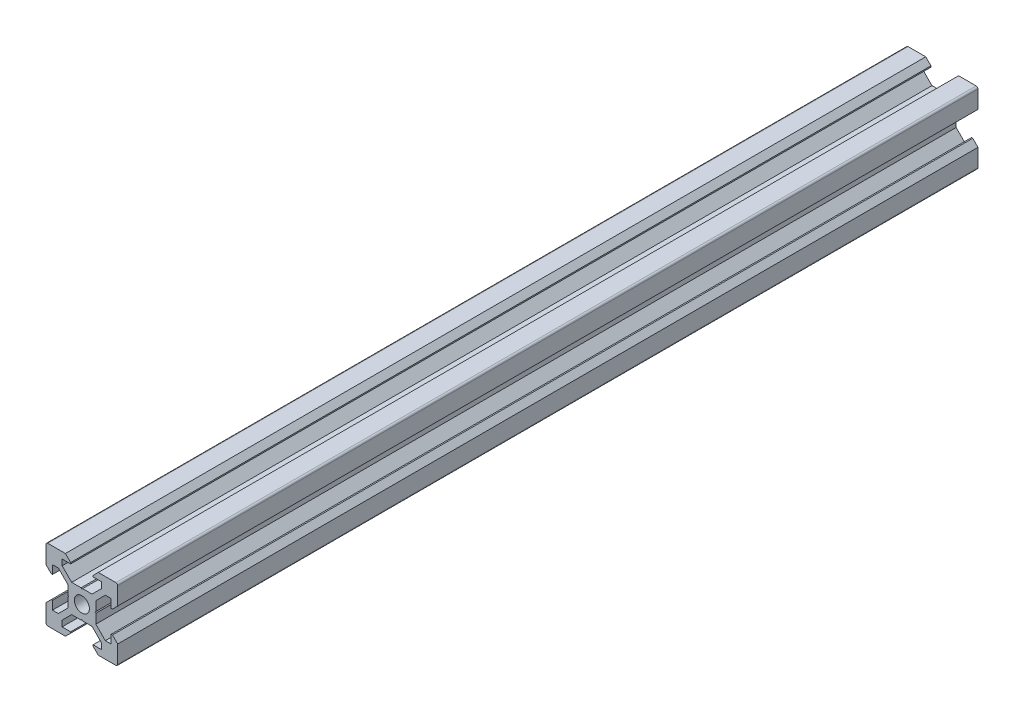
SolidWorks part; units mm, degrees
material "6061-T6 (SS)"
ref_plane "Front Plane" through (0, 0, 0) normal (0, 0, 1) x (1, 0, 0)
ref_plane "Top Plane" through (0, 0, 0) normal (0, 1, 0) x (1, 0, 0)
ref_plane "Right Plane" through (0, 0, 0) normal (1, 0, 0) x (0, 0, -1)
sketch "Sketch1" plane through (0, 0, 0) normal (0, 0, 1) x (1, 0, 0)
  line L1 (9.5, -10) -> (-9.5, -10)
  line L2 (10, -9.5) -> (10, 9.5)
  line L3 (9.5, 10) -> (-9.5, 10)
  line L4 (-10, -9.5) -> (-10, 9.5)
  line L5 (10, -10) -> (-10, 10) construction
  line L6 (10, 10) -> (-10, -10) construction
  circle A0 centre (0, 0) radius 2.1
  arc A1 (-9.5, 10) -> (-10, 9.5) centre (-9.5, 9.5) ccw
  arc A2 (10, 9.5) -> (9.5, 10) centre (9.5, 9.5) ccw
  arc A3 (9.5, -10) -> (10, -9.5) centre (9.5, -9.5) ccw
  arc A4 (-9.5, -10) -> (-10, -9.5) centre (-9.5, -9.5) cw
  point P0 (0, 0)
  line B0 (0, 0) -> (0, 10) construction
  line B1 (0, 3.69) -> (-0.21, 3.9)
  line B2 (-0.21, 3.9) -> (-2.8393, 3.9)
  line B3 (-2.8393, 3.9) -> (-5.5, 6.5607)
  line B4 (-5.5, 6.5607) -> (-5.5, 8.2)
  line B5 (-5.5, 8.2) -> (-3.125, 8.2)
  line B6 (-3.125, 8.2) -> (-3.125, 8.545)
  line B7 (-3.125, 8.545) -> (-4.58, 10)
  line B8 (-4.58, 10) -> (4.58, 10)
  line B9 (0, 0) -> (-5.9132, 5.9132) construction
  line B10 (3.125, 8.545) -> (4.58, 10)
  line B11 (3.125, 8.2) -> (3.125, 8.545)
  line B12 (5.5, 8.2) -> (3.125, 8.2)
  line B13 (5.5, 6.5607) -> (5.5, 8.2)
  line B14 (2.8393, 3.9) -> (5.5, 6.5607)
  line B15 (0.21, 3.9) -> (2.8393, 3.9)
  line B16 (0, 3.69) -> (0.21, 3.9)
  line B17 (0, 0) -> (-10, 0) construction
  line B18 (-3.69, 0) -> (-3.9, -0.21)
  line B19 (-3.9, -0.21) -> (-3.9, -2.8393)
  line B20 (-3.9, -2.8393) -> (-6.5607, -5.5)
  line B21 (-6.5607, -5.5) -> (-8.2, -5.5)
  line B22 (-8.2, -5.5) -> (-8.2, -3.125)
  line B23 (-8.2, -3.125) -> (-8.545, -3.125)
  line B24 (-8.545, -3.125) -> (-10, -4.58)
  line B25 (-10, -4.58) -> (-10, 4.58)
  line B26 (0, 0) -> (-5.9132, -5.9132) construction
  line B27 (-8.545, 3.125) -> (-10, 4.58)
  line B28 (-8.2, 3.125) -> (-8.545, 3.125)
  line B29 (-8.2, 5.5) -> (-8.2, 3.125)
  line B30 (-6.5607, 5.5) -> (-8.2, 5.5)
  line B31 (-3.9, 2.8393) -> (-6.5607, 5.5)
  line B32 (-3.9, 0.21) -> (-3.9, 2.8393)
  line B33 (-3.69, 0) -> (-3.9, 0.21)
  line B34 (0, 0) -> (0, -10) construction
  line B35 (0, -3.69) -> (0.21, -3.9)
  line B36 (0.21, -3.9) -> (2.8393, -3.9)
  line B37 (2.8393, -3.9) -> (5.5, -6.5607)
  line B38 (5.5, -6.5607) -> (5.5, -8.2)
  line B39 (5.5, -8.2) -> (3.125, -8.2)
  line B40 (3.125, -8.2) -> (3.125, -8.545)
  line B41 (3.125, -8.545) -> (4.58, -10)
  line B42 (4.58, -10) -> (-4.58, -10)
  line B43 (0, 0) -> (5.9132, -5.9132) construction
  line B44 (-3.125, -8.545) -> (-4.58, -10)
  line B45 (-3.125, -8.2) -> (-3.125, -8.545)
  line B46 (-5.5, -8.2) -> (-3.125, -8.2)
  line B47 (-5.5, -6.5607) -> (-5.5, -8.2)
  line B48 (-2.8393, -3.9) -> (-5.5, -6.5607)
  line B49 (-0.21, -3.9) -> (-2.8393, -3.9)
  line B50 (0, -3.69) -> (-0.21, -3.9)
  line B51 (0, 0) -> (10, 0) construction
  line B52 (3.69, 0) -> (3.9, 0.21)
  line B53 (3.9, 0.21) -> (3.9, 2.8393)
  line B54 (3.9, 2.8393) -> (6.5607, 5.5)
  line B55 (6.5607, 5.5) -> (8.2, 5.5)
  line B56 (8.2, 5.5) -> (8.2, 3.125)
  line B57 (8.2, 3.125) -> (8.545, 3.125)
  line B58 (8.545, 3.125) -> (10, 4.58)
  line B59 (10, 4.58) -> (10, -4.58)
  line B60 (0, 0) -> (5.9132, 5.9132) construction
  line B61 (8.545, -3.125) -> (10, -4.58)
  line B62 (8.2, -3.125) -> (8.545, -3.125)
  line B63 (8.2, -5.5) -> (8.2, -3.125)
  line B64 (6.5607, -5.5) -> (8.2, -5.5)
  line B65 (3.9, -2.8393) -> (6.5607, -5.5)
  line B66 (3.9, -0.21) -> (3.9, -2.8393)
  line B67 (3.69, 0) -> (3.9, -0.21)
  dimension "D1" = 4.2
  dimension "D3" = 0.5
  dimension "D2" = 20
sketch_block_instance "V Slot 1-4"
sketch_block "V Slot 1" parameters "D1"=10, "D2"=11, "D3"=4.3, "D4"=1.8, "D5"=0.21, "D6"=45, "D7"=9.16, "D8"=1.5, "D9"=6.25
sketch_block_instance "V Slot 1-5"
sketch_block_instance "V Slot 1-6"
sketch_block_instance "V Slot 1-7"
extrude "Boss-Extrude1" add sketch "Sketch1" along normal blind 240 contours B67 B52 B53 B54 B55 B56 B57 B58 L2 A2 L3 B10 B11 B12 B13 B14 B15 B16 B1 B2 B3 B4 B5 B6 B7 A1 L4 B27 B28 B29 B30 B31 B32 B33 B18 B19 B20 B21 B22 B23 B24 A4 L1 B44 B45 B46 B47 B48 B49
